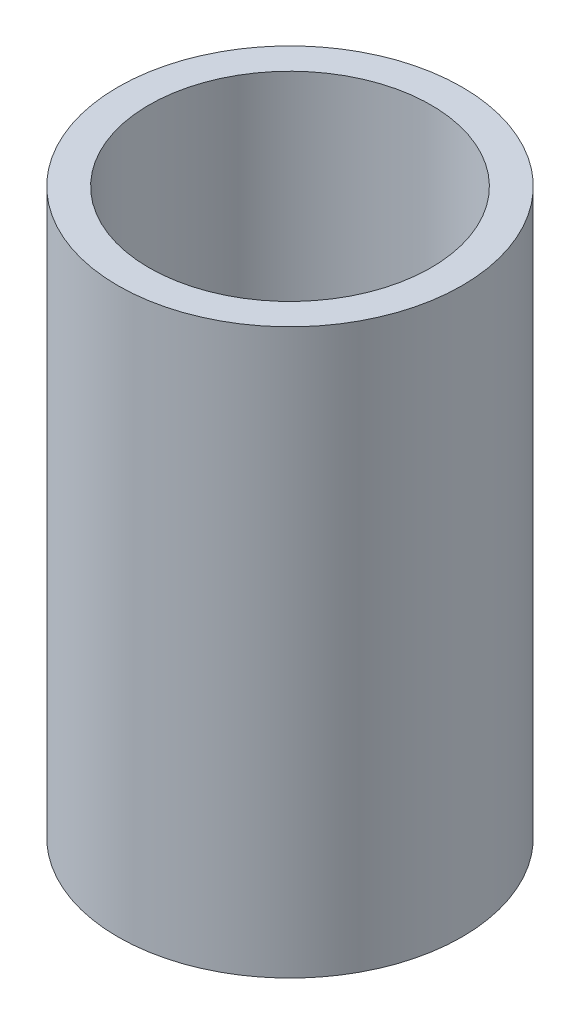
SolidWorks part; units mm, degrees
ref_plane "Front Plane" through (0, 0, 0) normal (0, 0, 1) x (1, 0, 0)
ref_plane "Top Plane" through (0, 0, 0) normal (0, 1, 0) x (1, 0, 0)
ref_plane "Right Plane" through (0, 0, 0) normal (1, 0, 0) x (0, 0, -1)
sketch "Sketch1" plane through (0, 0, 0) normal (0, 1, 0) x (1, 0, 0)
  circle A0 centre (0, 0) radius 3.05
  circle A1 centre (0, 0) radius 2.5
  dimension "D1" = 5
  dimension "D2" = 6.1
extrude "Boss-Extrude1" add sketch "Sketch1" along normal blind 9.5
sketch "Sketch2" plane through (0, 0, 0) normal (0, -1, 0) x (1, 0, 0)
  circle A0 centre (0, 0) radius 3.05 construction
  circle A1 centre (0, 0) radius 3.05
extrude "Boss-Extrude2" add sketch "Sketch2" along normal blind 0.5
